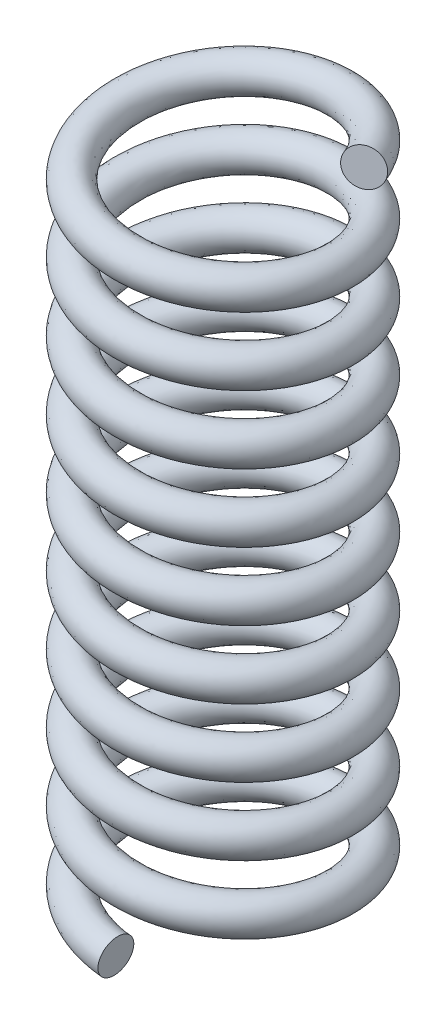
SolidWorks part; units mm, degrees
ref_plane "Front Plane" through (0, 0, 0) normal (0, 0, 1) x (1, 0, 0)
ref_plane "Top Plane" through (0, 0, 0) normal (0, 1, 0) x (1, 0, 0)
ref_plane "Right Plane" through (0, 0, 0) normal (1, 0, 0) x (0, 0, -1)
sketch "Sketch1" plane through (0, 0, 0) normal (0, 1, 0) x (1, 0, 0)
  circle A0 centre (0, 0) radius 30
  dimension "D1" = 60
curve "Helix/Spiral1" pitch 19 height 184 turns 9.6842
ref_plane "Plane1" through (0, 0, 30) normal (-0.995, 0.1003, 0) x (0, 0, 1)
sketch "Sketch4" plane through (0, 0, 30) normal (-0.995, 0.1003, 0) x (0, 0, 1)
  circle A0 centre (0, 0) radius 5
  dimension "D1" = 10
sweep "Sweep1" add profiles "Sketch4" path "Helix/Spiral1"
